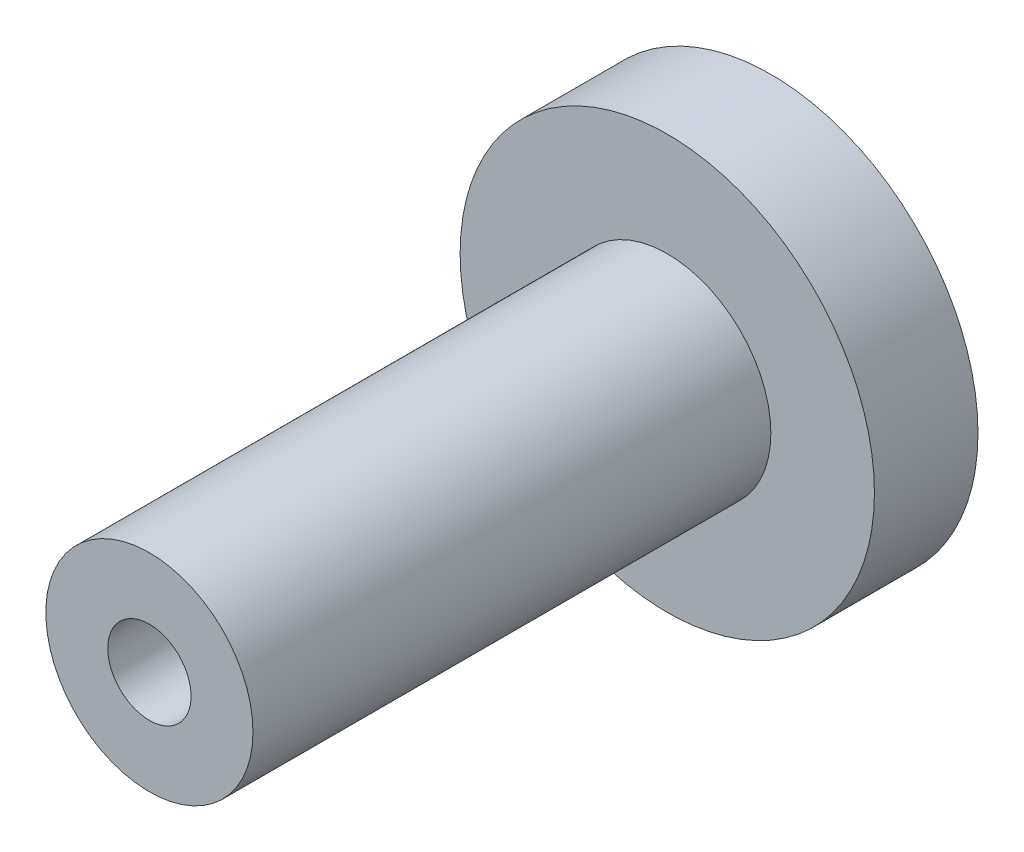
SolidWorks part; units mm, degrees
material "AISI 1020"
ref_plane "Front Plane" through (0, 0, 0) normal (0, 0, 1) x (1, 0, 0)
ref_plane "Top Plane" through (0, 0, 0) normal (0, 1, 0) x (1, 0, 0)
ref_plane "Right Plane" through (0, 0, 0) normal (1, 0, 0) x (0, 0, -1)
sketch "Sketch1" plane through (0, 0, 0) normal (0, 0, 1) x (1, 0, 0)
  circle A0 centre (0, 0) radius 12.7
  circle A1 centre (0, 0) radius 2.555
  dimension "D1" = 25.4
  dimension "D2" = 5.11
extrude "Boss-Extrude1" add sketch "Sketch1" along normal blind 38.1
cosmetic thread "Cosmetic Thread1"
sketch "Sketch2" plane through (0, 0, 38.1) normal (0, 0, 1) x (1, 0, 0)
  circle A0 centre (0, 0) radius 6.35
  circle A1 centre (0, 0) radius 12.7
  dimension "D1" = 12.7
extrude "Cut-Extrude1" cut sketch "Sketch2" against normal blind 31.75
